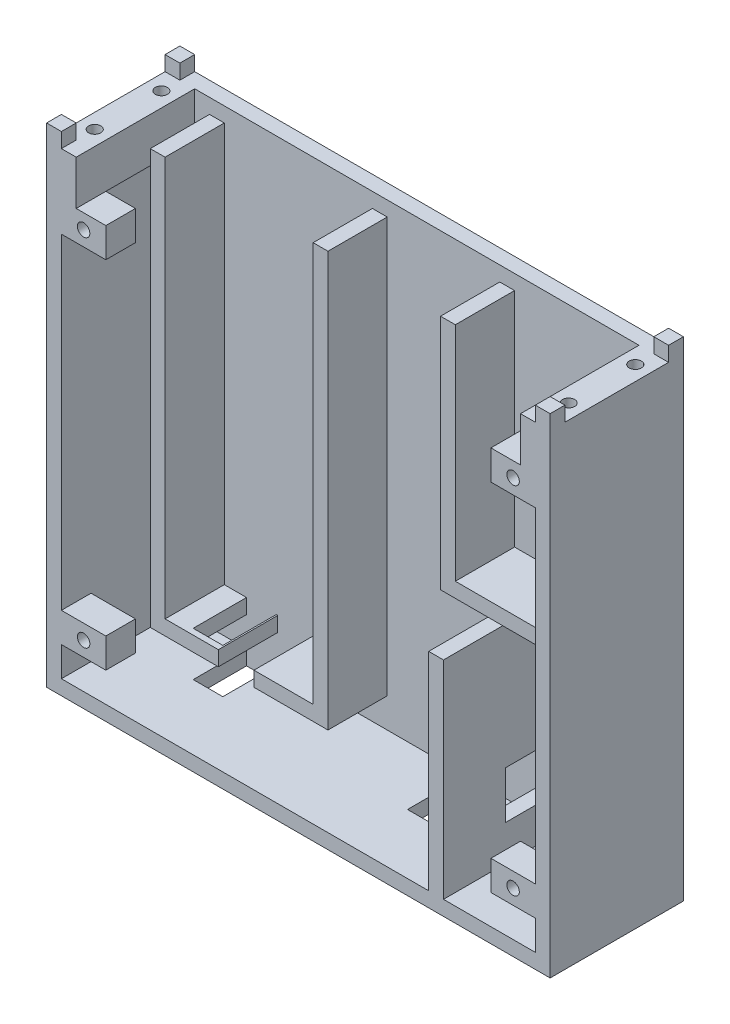
SolidWorks part; units mm, degrees
ref_plane "Alzado" through (0, 0, 0) normal (0, 0, 1) x (1, 0, 0)
ref_plane "Planta" through (0, 0, 0) normal (0, 1, 0) x (1, 0, 0)
ref_plane "Vista lateral" through (0, 0, 0) normal (1, 0, 0) x (0, 0, -1)
sketch "Croquis1" plane through (0, 0, 0) normal (0, 0, 1) x (1, 0, 0)
  line L0 (0, 47.7506) -> (0, 0) construction
  line L1 (0, 0) -> (-34.8896, 0) construction
  line L2 (-85, -80) -> (-85, 80)
  line L3 (-85, 80) -> (85, 80)
  line L4 (85, -80) -> (85, 80)
  line L5 (-85, -80) -> (85, -80)
  point P11 (0, 80)
  point P12 (-85, 0)
  point P13 (85, 0)
  dimension "D1" = 80
  dimension "D2" = 85
extrude "Saliente-Extruir1" add sketch "Croquis1" along normal blind 5
sketch "Croquis2" plane through (0, 0, 5) normal (0, 0, 1) x (1, 0, 0)
  line L0 (85, -80) -> (85, 80)
  line L1 (85, -80) -> (-85, -80)
  line L2 (-72.5, 65) -> (-72.5, 55) construction
  line L3 (-85, -80) -> (-85, 80)
  line L4 (-85, 80) -> (-80, 80)
  line L6 (-80, -75) -> (80, -75)
  line L7 (80, 80) -> (80, 75)
  line L8 (80, 80) -> (85, 80)
  line L13 (0, 0) -> (0, 44.2107) construction
  line L14 (-15.6091, 0) -> (0, 0) construction
  line L27 (80, 75) -> (80, 65)
  line L28 (-80, 80) -> (-80, 65)
  line L31 (-65, 55) -> (-80, 55)
  line L32 (-80, 65) -> (-65, 65)
  line L33 (-65, 65) -> (-65, 55)
  line L34 (-80, 55) -> (-80, -55)
  line L35 (80, 65) -> (65, 65)
  line L36 (65, 55) -> (80, 55)
  line L37 (65, 65) -> (65, 55)
  line L38 (65, -65) -> (65, -55)
  line L39 (80, -65) -> (65, -65)
  line L40 (65, -55) -> (80, -55)
  line L41 (-65, -65) -> (-65, -55)
  line L42 (-65, -55) -> (-80, -55)
  line L43 (-80, -65) -> (-65, -65)
  line L44 (80, 55) -> (80, -55)
  line L45 (80, -65) -> (80, -75)
  line L46 (-80, -65) -> (-80, -75)
  circle A0 centre (-72.5, 60) radius 2.1
  circle A1 centre (72.5, 60) radius 2.1
  circle A2 centre (72.5, -60) radius 2.1
  circle A3 centre (-72.5, -60) radius 2.1
  dimension "D1" = 4.2
  dimension "D2" = 5
  dimension "D3" = 5
  dimension "D5" = 10
  dimension "D6" = 55
  dimension "D7" = 65
extrude "Saliente-Extruir3" add sketch "Croquis2" along normal blind 40
sketch "Croquis3" plane through (0, 65, 0) normal (0, 1, 0) x (1, 0, 0)
  line L0 (-80, -35) -> (80, -35)
  line L1 (-80, -45) -> (-80, -5) construction
  line L2 (80, -45) -> (80, -5) construction
  line L3 (80, -35) -> (80, -5)
  line L4 (80, -5) -> (-80, -5)
  line L5 (-80, -5) -> (-80, -35)
  dimension "D1" = 30
extrude "Cortar-Extruir1" cut sketch "Croquis3" against normal up to surface (130 mm away) up to face at (72.5, -65, 25)
sketch "Croquis5" plane through (0, 0, 5) normal (0, 0, 1) x (1, 0, 0)
  line L0 (33, 75) -> (33, 0)
  line L1 (-70, 75) -> (-70, -65)
  line L3 (75, 0) -> (75, 75)
  line L5 (80, 75) -> (80, 2.6961)
  line L6 (80, 80) -> (80, -75) construction
  line L8 (28, -5) -> (28, 75)
  line L10 (75, 0) -> (74, 0)
  line L11 (74, 0) -> (74, 2.6961)
  line L12 (74, 2.6961) -> (80, 2.6961)
  line L13 (33, 0) -> (62, 0)
  line L14 (62, 0) -> (62, -5)
  line L15 (62, -5) -> (28, -5)
  line L19 (-10, -65) -> (-10, 75)
  line L21 (-15, 75) -> (-15, -60)
  line L22 (-15, -60) -> (-35, -60)
  line L23 (-65, -60) -> (-65, 75)
  line L25 (28, 75) -> (33, 75)
  line L26 (-47, -60) -> (-47, -65)
  line L27 (-35, -60) -> (-35, -65)
  line L28 (-47, -60) -> (-65, -60)
  line L29 (-35, -65) -> (-10, -65)
  line L31 (-15, 75) -> (-10, 75)
  line L32 (75, 75) -> (80, 75)
  line L34 (80, 80) -> (-80, 80) construction
  line L35 (-65, 75) -> (-70, 75)
  line L37 (-47, -65) -> (-70, -65)
  line L38 (-80, -65) -> (-65, -65) construction
  line M23 (80, -75) -> (80, 80)
  dimension "D1" = 5
  dimension "D2" = 5
  dimension "D3" = 29
  dimension "D4" = 12
  dimension "D5" = 42
  dimension "D6" = 50
  dimension "D7" = 5
  dimension "D8" = 5
  dimension "D9" = 135
  dimension "D10" = 18
  dimension "D11" = 20
  dimension "D12" = 38
  dimension "D13" = 5
  dimension "D14" = 80
  dimension "D15" = 5
extrude "Saliente-Extruir4" add sketch "Croquis5" along normal blind 20 contours L31 L21 L22 L27 L29 L19 | L25 L8 L15 L14 L13 L0 | L32 L3 L12 M23 | L23 L35 L1 L37 L26 L28
sketch "Croquis6" plane through (0, -80, 0) normal (0, -1, 0) x (1, 0, 0)
  line L0 (-57.5, 23) -> (-57.5, 5)
  line L1 (-57.5, 5) -> (-47.5, 5)
  line L2 (-47.5, 5) -> (-47.5, 23)
  line L3 (-47.5, 23) -> (-57.5, 23)
  line L4 (-85, 0) -> (85, 0) construction
  line L5 (-85, 45) -> (-85, 0) construction
  dimension "D1" = 5
  dimension "D2" = 18
  dimension "D3" = 10
  dimension "D4" = 27.5
extrude "Cortar-Extruir2" cut sketch "Croquis6" against normal blind 20
sketch "Croquis8" plane through (0, -80, 0) normal (0, -1, 0) x (1, 0, 0)
  line L2 (16.65, 24.8) -> (25, 24.8)
  line L3 (25, 24.8) -> (25, 11.8)
  line L4 (22.925, 9) -> (18.725, 9)
  line L5 (-85, 0) -> (85, 0) construction
  line L6 (16.65, 11.8) -> (18.725, 9)
  line L7 (22.925, 9) -> (25, 11.8)
  line L8 (20.825, 9) -> (20.825, 11.8) construction
  line L9 (16.65, 11.8) -> (25, 11.8) construction
  line L10 (16.65, 24.8) -> (16.65, 11.8)
  line L11 (-57.5, 23) -> (-57.5, 5) construction
  point P14 (20.825, 11.8)
  dimension "D1" = 82.5
  dimension "D2" = 8.35
  dimension "D3" = 15.8
  dimension "D4" = 9
  dimension "D5" = 13
  dimension "D6" = 2.1
  dimension "D7" = 2.1
extrude "Cortar-Extruir5" cut sketch "Croquis8" against normal blind 10 contours L2 L10 L6 L4 L7 L3
sketch "Croquis9" plane through (0, 0, 5) normal (0, 0, 1) x (1, 0, 0)
  line L1 (80, -75) -> (-47.5, -75) construction
  line L3 (80, -75) -> (-80, -75) construction
  line L6 (44, -5) -> (44, -75)
  line L10 (49, -5) -> (49, -75)
  line L11 (49, -75) -> (44, -75)
  line L17 (28, -5) -> (62, -5) construction
  line L18 (44, -5) -> (49, -5)
  dimension "D2" = 5
extrude "Saliente-Extruir5" add sketch "Croquis9" along normal blind 40
sketch "Croquis11" plane through (0, 0, 0) normal (0, 0, 1) x (1, 0, 0)
  line L0 (-85, 80) -> (-80, 80)
  line L3 (-85, 85) -> (-85, 80)
  line L4 (0, 0) -> (0, 87.7618) construction
  line L8 (-85, 85) -> (-80, 85)
  line L9 (-80, 85) -> (-80, 80)
  line L10 (85, 85) -> (80, 85)
  line L11 (85, 85) -> (85, 80)
  line L12 (85, 80) -> (80, 80)
  line L13 (80, 85) -> (80, 80)
  dimension "D1" = 5
extrude "Saliente-Extruir6" add sketch "Croquis11" along normal up to surface (45 mm away) up to face at (6.6429, -5.3571, 45)
sketch "Croquis12" plane through (49, 0, 0) normal (1, 0, 0) x (0, 0, -1)
  line L2 (-5, -75) -> (-5, -5) construction
  line L3 (-5, -63) -> (-5, -47)
  line L6 (-5, -47) -> (-24, -47)
  line L7 (-5, -63) -> (-24, -63)
  line L8 (-24, -63) -> (-24, -47)
  line L9 (-5, 78) -> (-5, -47) construction
  line L10 (-45, -75) -> (-5, -75) construction
  dimension "D1" = 19
  dimension "D2" = 16
  dimension "D3" = 125
  dimension "D4" = 12
extrude "Cortar-Extruir4" cut sketch "Croquis12" against normal blind 40
sketch "Croquis13" plane through (0, -80, 0) normal (0, -1, 0) x (1, 0, 0)
  line L0 (-85, 34.0927) -> (85, 34.0927) construction
  line L1 (-85, 45) -> (-85, 0) construction
  line L2 (85, 45) -> (85, 0) construction
  text T0 "Robot Rescue Batterys" font "Century Gothic" height in points 18
extrude "Saliente-Extruir7" add sketch "Croquis13" along normal blind 3
sketch "Croquis14" plane through (-85, 0, 0) normal (-1, 0, 0) x (0, 0, 1)
  line L0 (5, 85) -> (5, 80)
  line L1 (45, 85) -> (0, 85) construction
  line L2 (5, 80) -> (40, 80)
  line L3 (40, 80) -> (40, 85)
  line L4 (40, 85) -> (5, 85)
  line L5 (0, 85) -> (0, -80) construction
  line L6 (45, 85) -> (45, -80) construction
  dimension "D1" = 5
  dimension "D2" = 5
  dimension "D3" = 5
extrude "Cortar-Extruir6" cut sketch "Croquis14" against normal up to surface (170 mm away) up to face at (85, 2.5, 22.5)
sketch "Croquis15" plane through (0, 0, 5) normal (0, 0, 1) x (1, 0, 0)
  line L0 (-80, 80) -> (-75, 80)
  line L1 (80, 80) -> (-80, 80) construction
  line L2 (-80, 80) -> (-80, 65)
  line L3 (-80, 65) -> (-75, 65)
  line L4 (-65, 65) -> (-80, 65) construction
  line L5 (-75, 65) -> (-75, 80)
  line L6 (0, 80) -> (0, 54.2372) construction
  line L7 (80, 65) -> (75, 65)
  line L8 (80, 80) -> (80, 65)
  line L9 (80, 80) -> (75, 80)
  line L10 (75, 65) -> (75, 80)
  dimension "D1" = 5
extrude "Saliente-Extruir8" add sketch "Croquis15" along normal up to surface (40 mm away)
sketch "Croquis16" plane through (0, 80, 0) normal (0, 1, 0) x (1, 0, 0)
  line L0 (-80, 0) -> (-80, -22.5) construction
  line L1 (-80, -22.5) -> (-85, -22.5) construction
  line L2 (-85, -5) -> (-85, -40) construction
  line L3 (0, 0) -> (0, -26.6843) construction
  circle A0 centre (-80, -11.25) radius 2.05
  circle A1 centre (-80, -33.75) radius 2.05
  circle A2 centre (80, -33.75) radius 2.05
  circle A3 centre (80, -11.25) radius 2.05
  dimension "D1" = 4.1
extrude "Cortar-Extruir7" cut sketch "Croquis16" against normal blind 20
